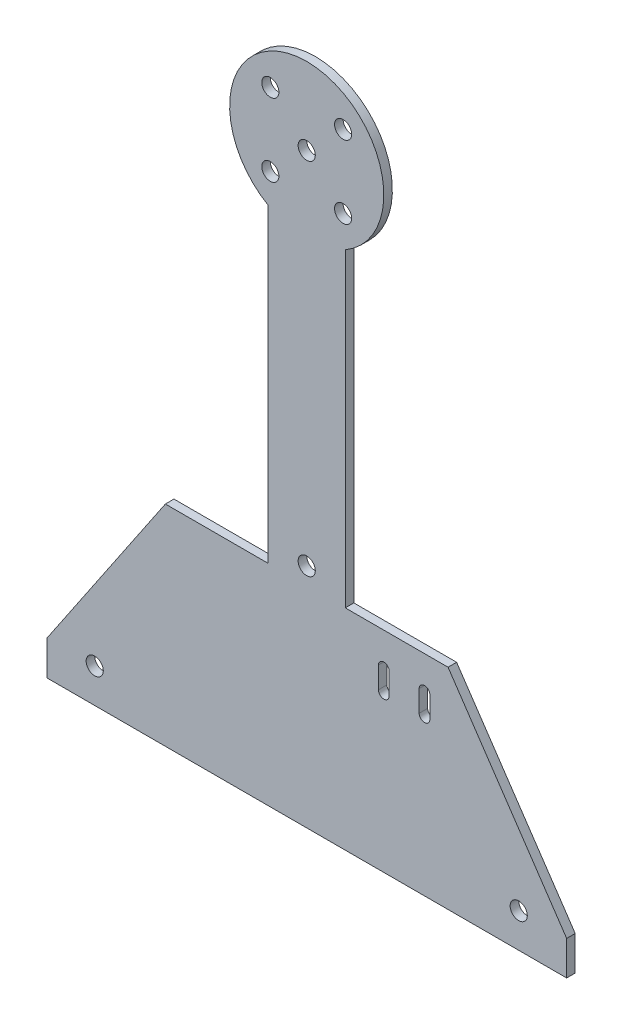
SolidWorks part; units mm, degrees
ref_plane "前视基准面" through (0, 0, 0) normal (0, 0, 1) x (1, 0, 0)
ref_plane "上视基准面" through (0, 0, 0) normal (0, 1, 0) x (1, 0, 0)
ref_plane "右视基准面" through (0, 0, 0) normal (1, 0, 0) x (0, 0, -1)
sketch "草图1" plane through (0, 0, 0) normal (0, 0, 1) x (1, 0, 0)
  line L0 (-49.7914, -7.3543) -> (-16.7914, -7.3543) construction
  line L1 (-33.2914, -7.3543) -> (-33.2914, 7.6457) construction
  line L2 (-0.2914, 7.6457) -> (-0.2914, 121.6457) construction
  line L3 (-0.2914, 121.6457) -> (5.7086, 121.6457) construction
  line L4 (-9.2914, 33.6457) -> (-9.2914, 106.0573)
  line L5 (-9.2914, 33.6457) -> (-33.2914, 33.6457)
  line L6 (-33.2914, 33.6457) -> (-60.9865, -7.3543)
  line L7 (-60.9865, -7.3543) -> (-60.9865, -15.3543)
  line L8 (-60.9865, -15.3543) -> (0, -15.3543)
  line L9 (60.4036, -15.3543) -> (-0.5829, -15.3543)
  line L10 (60.4036, -7.3543) -> (60.4036, -15.3543)
  line L11 (32.7086, 33.6457) -> (60.4036, -7.3543)
  line L12 (8.7086, 33.6457) -> (32.7086, 33.6457)
  line L13 (8.7086, 33.6457) -> (8.7086, 106.0573)
  line L14 (-0.2914, 121.6457) -> (-0.2914, 130.1457) construction
  line L15 (-0.2914, 130.1457) -> (8.2086, 130.1457) construction
  line L16 (17.7031, 23.4457) -> (27.2031, 23.4457) construction
  line L17 (17.7031, 25.9457) -> (17.7031, 20.9457) construction
  line L18 (18.9531, 25.9457) -> (18.9531, 20.9457)
  line L19 (16.4531, 25.9457) -> (16.4531, 20.9457)
  line L20 (27.2031, 25.9457) -> (27.2031, 20.9457) construction
  line L21 (28.4531, 25.9457) -> (28.4531, 20.9457)
  line L22 (25.9531, 25.9457) -> (25.9531, 20.9457)
  circle A0 centre (16.2086, -7.3543) radius 2 construction
  circle A1 centre (-16.7914, -7.3543) radius 2 construction
  circle A2 centre (49.2086, -7.3543) radius 2
  circle A3 centre (-49.7914, -7.3543) radius 2
  circle A4 centre (-33.2914, 7.6457) radius 2 construction
  circle A5 centre (32.7086, 7.6457) radius 2 construction
  circle A6 centre (-0.2914, 7.6457) radius 2 construction
  circle A11 centre (8.2086, 130.1457) radius 2
  circle A12 centre (-0.2914, 37.6457) radius 2
  circle A13 centre (8.2086, 113.1457) radius 2
  circle A14 centre (-8.7914, 113.1457) radius 2
  circle A15 centre (-8.7914, 130.1457) radius 2
  circle A16 centre (-0.2914, 121.6457) radius 18 construction
  arc A17 (-9.2914, 106.0573) -> (8.7086, 106.0573) centre (-0.2914, 121.6457) cw
  circle A18 centre (-0.2914, 121.6457) radius 2
  arc A19 (18.9531, 25.9457) -> (16.4531, 25.9457) centre (17.7031, 25.9457) ccw
  arc A20 (16.4531, 20.9457) -> (18.9531, 20.9457) centre (17.7031, 20.9457) ccw
  arc A21 (28.4531, 25.9457) -> (25.9531, 25.9457) centre (27.2031, 25.9457) ccw
  arc A22 (25.9531, 20.9457) -> (28.4531, 20.9457) centre (27.2031, 20.9457) ccw
  point P48 (17.7031, 23.4457)
  point P55 (27.2031, 23.4457)
  dimension "D1" = 114
  dimension "D5" = 30
  dimension "D6" = 4
  dimension "D7" = 4
  dimension "D8" = 8
  dimension "D3" = 9.5
  dimension "D10" = 10.2
  dimension "D2" = 24
  dimension "D4" = 8
  dimension "D9" = 137
extrude "凸台-拉伸1" add sketch "草图1" along normal blind 2
sketch "草图2" plane through (0, 0, 2) normal (0, 0, 1) x (1, 0, 0)
  line L0 (17.7031, 25.9457) -> (17.7031, 20.9457)
  line L1 (27.2031, 25.9457) -> (27.2031, 20.9457)
